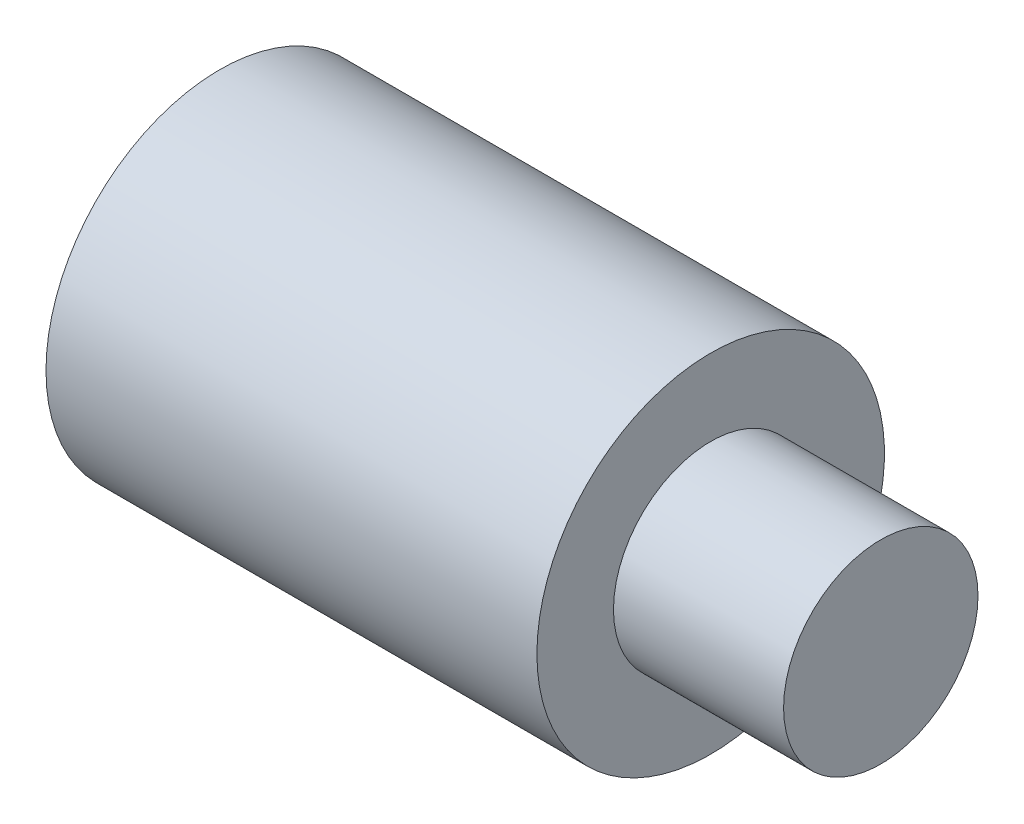
SolidWorks part; units mm, degrees
ref_plane "Front Plane" through (0, 0, 0) normal (0, 0, 1) x (1, 0, 0)
ref_plane "Top Plane" through (0, 0, 0) normal (0, 1, 0) x (1, 0, 0)
ref_plane "Right Plane" through (0, 0, 0) normal (1, 0, 0) x (0, 0, -1)
sketch "Sketch1" plane through (0, 0, 0) normal (0, 0, 1) x (1, 0, 0)
  line L1 (0, 1.5) -> (0, 0)
  line L2 (0, 0) -> (8.6, 0)
  line L3 (8.6, -2.075) -> (8.6, 0)
  line L6 (8.6, -2.075) -> (13.6, -2.075)
  line L7 (13.6, -2.075) -> (13.6, -0.075)
  line L8 (13.6, -0.075) -> (10.1, -0.075)
  line L9 (10.1, -0.075) -> (10.1, 1.5)
  line L10 (10.1, 1.5) -> (0, 1.5)
  dimension "D1" = 10.1
  dimension "D2" = 3.5
  dimension "D3" = 2.075
  dimension "D4" = 2
  dimension "D5" = 1.5
  dimension "D7" = 1.5
revolve "Revolve1" add sketch "Sketch1" angle 360 about L6
